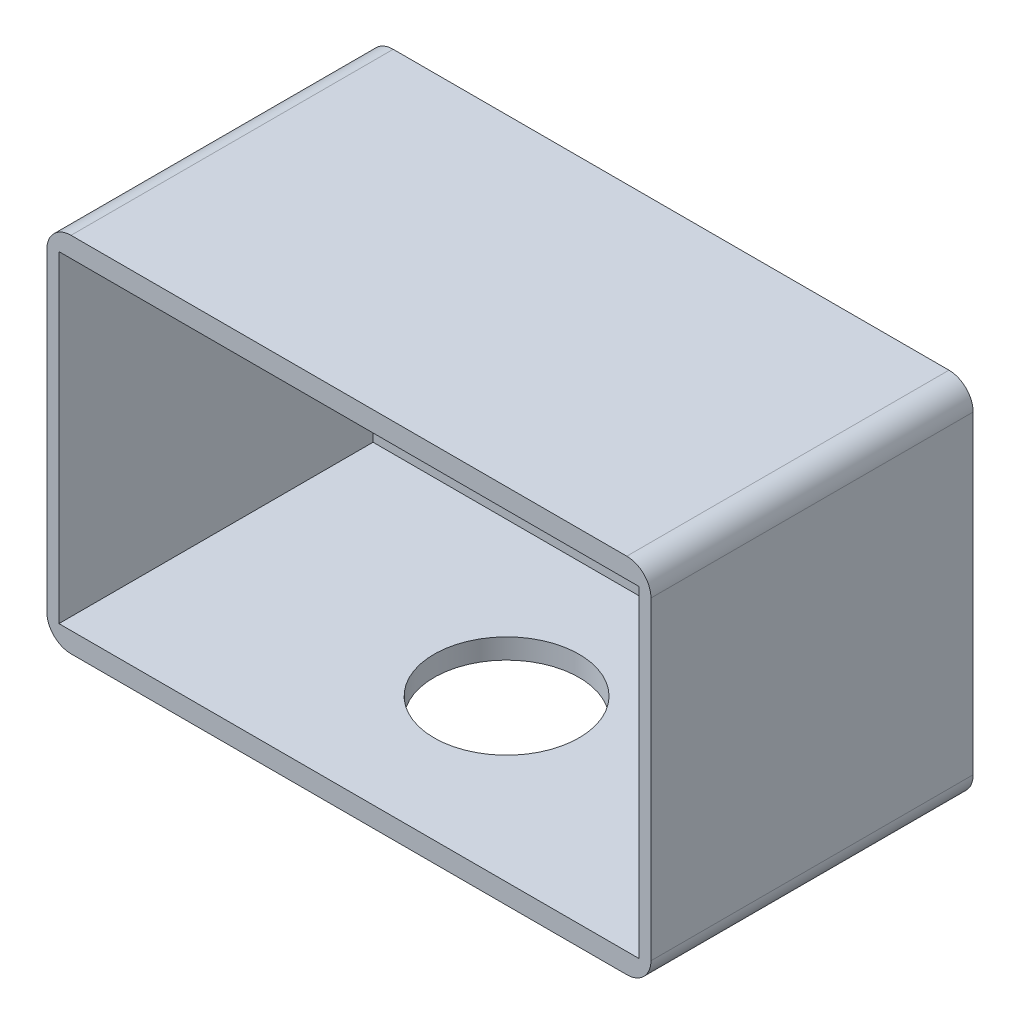
SolidWorks part; units mm, degrees
ref_plane "Front Plane" through (0, 0, 0) normal (0, 0, 1) x (1, 0, 0)
ref_plane "Top Plane" through (0, 0, 0) normal (0, 1, 0) x (1, 0, 0)
ref_plane "Right Plane" through (0, 0, 0) normal (1, 0, 0) x (0, 0, -1)
sketch "Sketch1" plane through (0, 0, 0) normal (0, 0, 1) x (1, 0, 0)
  line L1 (-36, -20) -> (36, -20)
  line L2 (-36, -20) -> (-36, 20)
  line L3 (-36, 20) -> (36, 20)
  line L4 (36, -20) -> (36, 20)
  line L9 (-34.5, -22.5) -> (34.5, -22.5)
  line L10 (-37.5, -19.5) -> (-37.5, 19.5)
  line L11 (-34.5, 22.5) -> (34.5, 22.5)
  line L12 (37.5, -19.5) -> (37.5, 19.5)
  arc A4 (-34.5, -22.5) -> (-37.5, -19.5) centre (-34.5, -19.5) cw
  arc A5 (34.5, -22.5) -> (37.5, -19.5) centre (34.5, -19.5) ccw
  arc A6 (34.5, 22.5) -> (37.5, 19.5) centre (34.5, 19.5) cw
  arc A7 (-37.5, 19.5) -> (-34.5, 22.5) centre (-34.5, 19.5) cw
  point P0 (0, 0)
  point P6 (0, 0)
  point P8 (0, 0)
  point P16 (37.5, -22.5)
  point P19 (37.5, 22.5)
  point P22 (-37.5, 22.5)
  dimension "D5" = 3
  dimension "D1" = 72
  dimension "D2" = 40
  dimension "D3" = 75
  dimension "D4" = 45
extrude "Boss-Extrude2" add sketch "Sketch1" along normal blind 40
sketch "Sketch3" plane through (0, -20, 0) normal (0, 1, 0) x (1, 0, 0)
  circle A1 centre (-0.4251, -20) radius 9
  dimension "D2" = 18
extrude "Cut-Extrude2" cut sketch "Sketch3" against normal blind 4
sketch "Sketch7" plane through (0, 0, 0) normal (0, 0, 1) x (1, 0, 0)
  line L1 (-36, -20) -> (36, -20)
  line L2 (-36, -20) -> (-36, 20)
  line L3 (-36, 20) -> (36, 20)
  line L4 (36, -20) -> (36, 20)
  line L5 (-36, -20) -> (36, 20) construction
  line L6 (-36, 20) -> (36, -20) construction
  point P0 (0, 0)
extrude "Boss-Extrude5" add sketch "Sketch7" along normal blind 1
